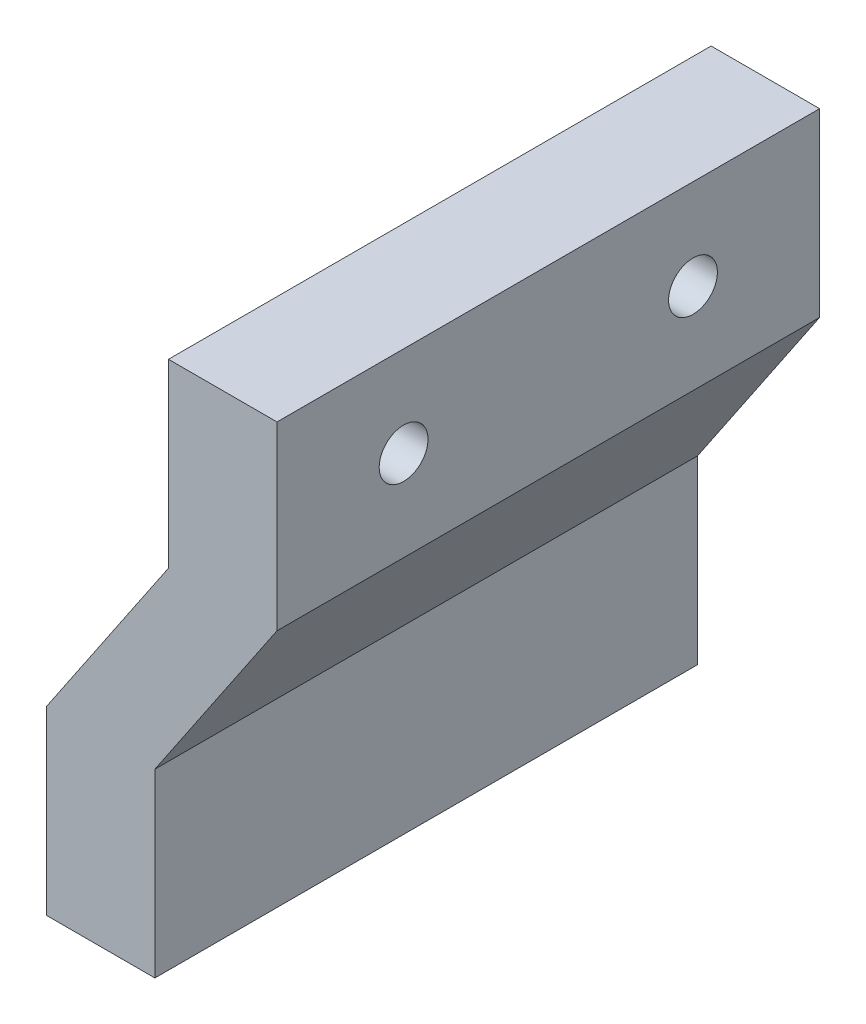
SolidWorks part; units mm, degrees
ref_plane "Front Plane" through (0, 0, 0) normal (0, 0, 1) x (1, 0, 0)
ref_plane "Top Plane" through (0, 0, 0) normal (0, 1, 0) x (1, 0, 0)
ref_plane "Right Plane" through (0, 0, 0) normal (1, 0, 0) x (0, 0, -1)
sketch "Sketch1" plane through (0, 0, 0) normal (0, 0, 1) x (1, 0, 0)
  line L8 (0, 0) -> (6, 0)
  line L9 (6, 0) -> (6, 10)
  line L10 (6, 10) -> (12.75, 20)
  line L11 (12.75, 20) -> (12.75, 30)
  line L12 (12.75, 30) -> (6.75, 30)
  line L13 (6.75, 30) -> (6.75, 20)
  line L14 (6.75, 20) -> (0, 10)
  line L15 (0, 10) -> (0, 0)
  point P7 (12.75, 25)
  dimension "D1" = 6
  dimension "D2" = 12.75
  dimension "D3" = 30
  dimension "D4" = 10
  dimension "D5" = 10
extrude "Boss-Extrude1" add sketch "Sketch1" along normal blind 30
sketch "Sketch2" plane through (0, 0, 0) normal (0, -1, 0) x (1, 0, 0)
  line L0 (0, 30) -> (0, 0) construction
  line L1 (0, 30) -> (6, 30) construction
  line L2 (0, 0) -> (6, 0) construction
  circle A0 centre (3, 26.5) radius 1.35
  circle A1 centre (3, 3.5) radius 1.35
  dimension "D1" = 2.7
  dimension "D2" = 3
  dimension "D3" = 3.5
  dimension "D4" = 3.5
  dimension "D5" = 23
extrude "Cut-Extrude1" cut sketch "Sketch2" against normal blind 8.5
sketch "Sketch3" plane through (6.75, 0, 0) normal (-1, 0, 0) x (0, 0, 1)
  line L2 (30, 30) -> (0, 30) construction
  line L3 (0, 30) -> (0, 20) construction
  line L4 (30, 30) -> (30, 20) construction
  circle A0 centre (7, 25) radius 1.35
  circle A1 centre (23, 25) radius 1.35
  dimension "D1" = 2.7
  dimension "D2" = 16
  dimension "D3" = 7
  dimension "D4" = 5
  dimension "D5" = 7
extrude "Cut-Extrude2" cut sketch "Sketch3" against normal up to next
